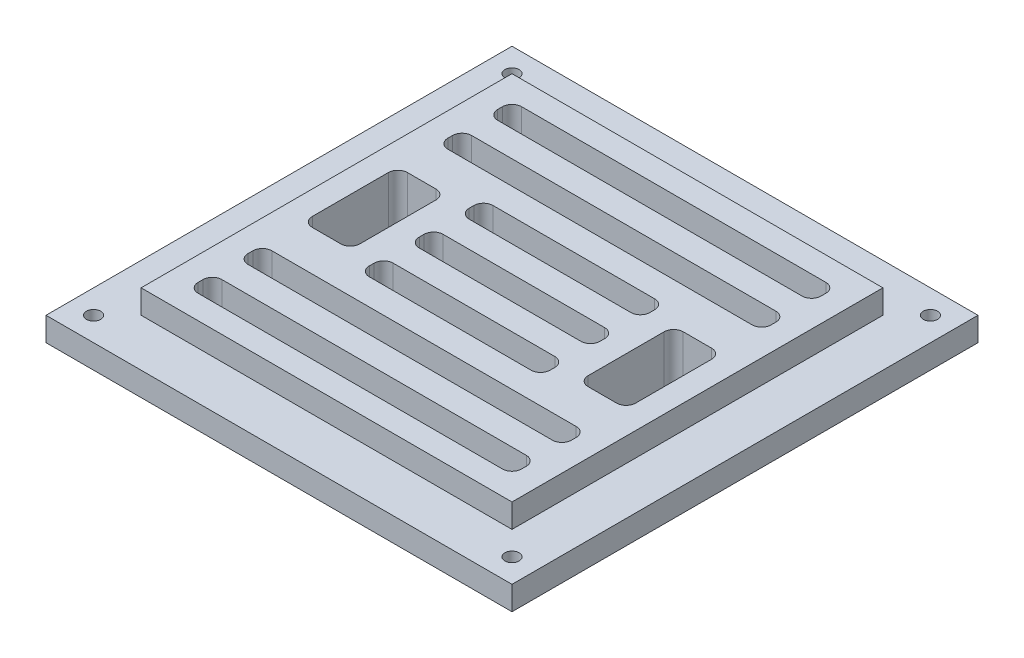
SolidWorks part; units mm, degrees
ref_plane "Front Plane" through (0, 0, 0) normal (0, 0, 1) x (1, 0, 0)
ref_plane "Top Plane" through (0, 0, 0) normal (0, 1, 0) x (1, 0, 0)
ref_plane "Right Plane" through (0, 0, 0) normal (1, 0, 0) x (0, 0, -1)
sketch "Sketch1" plane through (0, 0, 0) normal (0, 1, 0) x (1, 0, 0)
  line L1 (-49, 49) -> (49, 49)
  line L2 (-49, 49) -> (-49, -49)
  line L3 (-49, -49) -> (49, -49)
  line L4 (49, 49) -> (49, -49)
  line L6 (-49, -49) -> (49, 49) construction
  line L9 (0, 0) -> (49, -49) construction
  point P0 (0, 0)
  dimension "D1" = 98
  dimension "D2" = 98
extrude "Boss-Extrude1" add sketch "Sketch1" along normal blind 10
sketch "Sketch4" plane through (0, 10, 0) normal (0, 1, 0) x (1, 0, 0)
  line L1 (44, -44) -> (-44, -44)
  line L2 (44, -44) -> (44, 44)
  line L3 (44, 44) -> (-44, 44)
  line L4 (-44, -44) -> (-44, 44)
  line L7 (-44, 40.4645) -> (-3.5355, 0)
  line L8 (-40.4645, 44) -> (0, 3.5355)
  line L10 (40.4645, 44) -> (0, 3.5355)
  line L11 (44, 40.4645) -> (3.5355, 0)
  line L12 (0, -3.5355) -> (40.4645, -44)
  line L13 (3.5355, 0) -> (44, -40.4645)
  line L14 (0, -3.5355) -> (-40.4645, -44)
  line L15 (-3.5355, 0) -> (-44, -40.4645)
  point P0 (0, 0)
  point P16 (-1.7678, 1.7678)
  dimension "D1" = 88
  dimension "D2" = 88
sketch "Sketch5" plane through (0, 10, 0) normal (0, 1, 0) x (1, 0, 0)
  line L0 (-44, -44) -> (-44, -39) construction
  line L1 (-44, -44) -> (44, -44) construction
  line L2 (-44, -44) -> (-44, 44) construction
  line L3 (-44, 44) -> (44, 44) construction
  line L4 (44, -44) -> (44, 44) construction
  line L5 (-6, 11.5) -> (-6, -39)
  line L6 (-6, -39) -> (-44, -39)
  line L7 (-44, -39) -> (-44, 11.5)
  line L8 (-44, 11.5) -> (-6, 11.5)
  point P0 (0, 0)
sketch "Sketch7" plane through (0, 10, 0) normal (0, 1, 0) x (1, 0, 0)
  line L1 (39, 39) -> (-39, 39)
  line L2 (39, 39) -> (39, -39)
  line L3 (39, -39) -> (-39, -39)
  line L4 (-39, 39) -> (-39, -39)
  line L5 (39, 39) -> (-39, -39) construction
  line L6 (39, -39) -> (-39, 39) construction
  line L7 (49, 49) -> (-49, 49)
  line L8 (49, 49) -> (49, -49)
  line L9 (49, -49) -> (-49, -49)
  line L10 (-49, 49) -> (-49, -49)
  line L11 (49, 49) -> (-49, -49) construction
  line L12 (49, -49) -> (-49, 49) construction
  point P0 (0, 0)
  point P6 (0, 0)
sketch "Sketch8" plane through (0, 10, 0) normal (0, 1, 0) x (1, 0, 0)
  line L1 (49, 49) -> (-49, 49)
  line L2 (49, 49) -> (49, -49)
  line L3 (49, -49) -> (-49, -49)
  line L4 (-49, 49) -> (-49, -49)
  line L5 (39, 39) -> (-39, 39)
  line L6 (39, 39) -> (39, -39)
  line L7 (39, -39) -> (-39, -39)
  line L8 (-39, 39) -> (-39, -39)
  line L9 (39, 39) -> (-39, -39) construction
  line L10 (39, -39) -> (-39, 39) construction
  point P0 (0, 0)
  point P7 (0, 0)
  dimension "D1" = 78
  dimension "D2" = 78
extrude "Cut-Extrude5" cut sketch "Sketch8" against normal blind 5
sketch "Sketch14" plane through (0, 0, 0) normal (0, -1, 0) x (1, 0, 0)
  line L0 (-44, 0) -> (-35.5474, 0)
  line L1 (44, 44) -> (-44, 44) construction
  line L2 (44, 44) -> (44, -44) construction
  line L3 (44, -44) -> (-44, -44) construction
  line L4 (-44, 44) -> (-44, -44) construction
  line L5 (0, -44) -> (0, -38.0642)
  circle A0 centre (-44, -44) radius 1.5
  circle A1 centre (-44, 44) radius 1.5
  circle A2 centre (44, 44) radius 1.5
  circle A3 centre (44, -44) radius 1.5
  point P0 (0, 0)
  dimension "D1" = 3
extrude "Cut-Extrude11" cut sketch "Sketch14" against normal blind 10 contours A0 | A1 | A2 | A3
sketch "Sketch15" plane through (0, 10, 0) normal (0, 1, 0) x (1, 0, 0)
  line L0 (34, 10) -> (34, 15)
  line L1 (24, 10) -> (24, -10)
  line L2 (24, 10) -> (34, 10)
  line L3 (24, -10) -> (34, -10)
  line L4 (32, 34) -> (-32, 34)
  line L5 (34, 32) -> (34, 31) construction
  line L6 (32, -34) -> (-32, -34)
  line L7 (-34, 32) -> (-34, 31) construction
  line L8 (-19, 0.5) -> (-19, -0.5)
  line L9 (34, -10) -> (34, -15) construction
  line L10 (34, -15) -> (19, -15)
  line L11 (19, 11) -> (19, 10)
  line L12 (34, 10) -> (34, -10)
  line L14 (-19, 11) -> (-19, 10)
  line L16 (-24, -10) -> (-34, -10)
  line L17 (-24, 10) -> (-24, -10)
  line L18 (-24, 10) -> (-34, 10)
  line L22 (34, -29) -> (34, -34) construction
  line L24 (14, 2.5) -> (-14, 2.5)
  line L26 (14, -2.5) -> (-14, -2.5)
  line L28 (14, 8) -> (-14, 8)
  line L30 (14, 13) -> (-14, 13)
  line L32 (14, 18.5) -> (-14, 18.5)
  line L34 (14, 23.5) -> (-14, 23.5)
  line L36 (14, 29) -> (-14, 29)
  line L38 (14, 34) -> (-14, 34)
  line L40 (14, -13) -> (-14, -13)
  line L42 (14, -8) -> (-14, -8)
  line L44 (14, -23.5) -> (-14, -23.5)
  line L46 (14, -18.5) -> (-14, -18.5)
  line L48 (14, -34) -> (-14, -34)
  line L50 (14, -29) -> (-14, -29)
  line L51 (14, 18.5) -> (32, 18.5)
  line L52 (14, 29) -> (32, 29)
  line L54 (14, 34) -> (32, 34)
  line L55 (34, 31) -> (34, 32)
  line L56 (-14, 29) -> (-32, 29)
  line L58 (-14, 34) -> (-34, 34)
  line L59 (-34, 31) -> (-34, 32)
  line L60 (14, -29) -> (32, -29)
  line L62 (14, -34) -> (34, -34)
  line L63 (34, -31) -> (34, -32)
  line L64 (-14, -29) -> (-32, -29)
  line L66 (-14, -34) -> (-32, -34)
  line L67 (-34, -31) -> (-34, -32)
  line L69 (14, 23.5) -> (32, 23.5)
  line L70 (34, 20.5) -> (34, 21.5)
  line L71 (-14, 23.5) -> (-32, 23.5)
  line L73 (-14, 18.5) -> (-32, 18.5)
  line L74 (-34, 21.5) -> (-34, 20.5)
  line L75 (14, 13) -> (17, 13)
  line L77 (14, 8) -> (17, 8)
  line L78 (19, 11) -> (19, 10)
  line L79 (14, 2.5) -> (17, 2.5)
  line L81 (14, -2.5) -> (17, -2.5)
  line L82 (19, 0.5) -> (19, -0.5)
  line L83 (-14, 13) -> (-17, 13)
  line L85 (-14, 8) -> (-17, 8)
  line L86 (-19, 13) -> (-19, 8)
  line L87 (-14, 2.5) -> (-17, 2.5)
  line L89 (-14, -2.5) -> (-17, -2.5)
  line L90 (-19, 2.5) -> (-19, -2.5)
  line L91 (-14, -8) -> (-17, -8)
  line L93 (-14, -13) -> (-17, -13)
  line L94 (-19, -10) -> (-19, -11)
  line L95 (14, -8) -> (17, -8)
  line L97 (14, -13) -> (17, -13)
  line L98 (19, -10) -> (19, -11)
  line L99 (14, -18.5) -> (32, -18.5)
  line L101 (14, -23.5) -> (32, -23.5)
  line L102 (34, -20.5) -> (34, -21.5)
  line L103 (-14, -18.5) -> (-32, -18.5)
  line L105 (-14, -23.5) -> (-32, -23.5)
  line L106 (-34, -20.5) -> (-34, -21.5)
  line L107 (-34, 10) -> (-34, -10)
  line L108 (34, -18.5) -> (34, -23.5) construction
  line L113 (-34, 10) -> (-34, -10) construction
  line L115 (34, 15) -> (34, 10) construction
  line L117 (-34, 21.5) -> (-34, 20.5) construction
  line L118 (34, 21.5) -> (34, 20.5) construction
  line L119 (19, 0.5) -> (19, -0.5)
  line L120 (19, -8) -> (19, -13)
  line L121 (-34, -31) -> (-34, -32) construction
  line L122 (-19, -8) -> (-19, -15)
  line L124 (-34, -20.5) -> (-34, -21.5) construction
  arc A0 (17, -2.5) -> (19, -0.5) centre (17, -0.5) ccw
  arc A1 (17, 2.5) -> (19, 0.5) centre (17, 0.5) cw
  arc A2 (17, 8) -> (19, 10) centre (17, 10) ccw
  arc A3 (17, 13) -> (19, 11) centre (17, 11) cw
  arc A4 (32, 18.5) -> (34, 20.5) centre (32, 20.5) ccw
  arc A5 (32, 23.5) -> (34, 21.5) centre (32, 21.5) cw
  arc A6 (32, 29) -> (34, 31) centre (32, 31) ccw
  arc A7 (32, 34) -> (34, 32) centre (32, 32) cw
  arc A8 (-34, -32) -> (-32, -34) centre (-32, -32) ccw
  arc A9 (-34, -31) -> (-32, -29) centre (-32, -31) cw
  arc A10 (-34, -21.5) -> (-32, -23.5) centre (-32, -21.5) ccw
  arc A11 (-34, -20.5) -> (-32, -18.5) centre (-32, -20.5) cw
  arc A12 (-34, 20.5) -> (-32, 18.5) centre (-32, 20.5) ccw
  arc A13 (-34, 21.5) -> (-32, 23.5) centre (-32, 21.5) cw
  arc A14 (-34, 31) -> (-32, 29) centre (-32, 31) ccw
  arc A15 (-34, 32) -> (-32, 34) centre (-32, 32) cw
  arc A16 (32, -34) -> (34, -32) centre (32, -32) ccw
  arc A17 (32, -29) -> (34, -31) centre (32, -31) cw
  arc A18 (32, -23.5) -> (34, -21.5) centre (32, -21.5) ccw
  arc A19 (32, -18.5) -> (34, -20.5) centre (32, -20.5) cw
  arc A20 (17, -13) -> (19, -11) centre (17, -11) ccw
  arc A21 (17, -8) -> (19, -10) centre (17, -10) cw
  arc A22 (-19, -11) -> (-17, -13) centre (-17, -11) ccw
  arc A23 (-19, -10) -> (-17, -8) centre (-17, -10) cw
  arc A24 (-19, -0.5) -> (-17, -2.5) centre (-17, -0.5) ccw
  arc A25 (-19, 0.5) -> (-17, 2.5) centre (-17, 0.5) cw
  arc A26 (-19, 10) -> (-17, 8) centre (-17, 10) ccw
  arc A27 (-19, 11) -> (-17, 13) centre (-17, 11) cw
  point P5 (-1.7678, -1.7678)
  point P6 (0, 0)
  point P12 (34, 0)
  point P13 (24, 0)
  point P17 (1.7678, -1.7678)
  point P23 (-19, -13)
  point P26 (34, 0)
  point P34 (14, -2.5)
  point P37 (-14, -2.5)
  dimension "D5" = 2
  dimension "D1" = 2
  dimension "D2" = 2
  dimension "D3" = 4
  dimension "D4" = 4
extrude "Cut-Extrude19" cut sketch "Sketch15" against normal blind 10 contours A15 L59 A14 L56 L36 L52 A6 L55 A7 L4 | A13 L74 A12 L73 L32 L51 A4 L70 A5 L69 L34 L71 | A27 L14 A26 L85 L28 L77 A2 L11 A3 L75 L30 L83 | A25 L8 A24 L89 L26 L81 A0 L82 A1 L79 L24 L87 | A23 L94 A22 L93 L40 L97 A20 L98 A21 L95 L42 L91 | A19 L99 L46 L103 A11 L106 A10 L105 L44 L101 A18 L102 | A17 L60 L50 L64 A9 L67 A8 L6 A16 L63 | L18 L107 L16 L17 | L12 L2 L1 L3
fillet "Fillet1" radius 2 8 edges at (-34, 5, -10) (-34, 5, 10) (-24, 5, 10) (-24, 5, -10) (24, 5, 10) (24, 5, -10) (34, 5, 10) (34, 5, -10)
